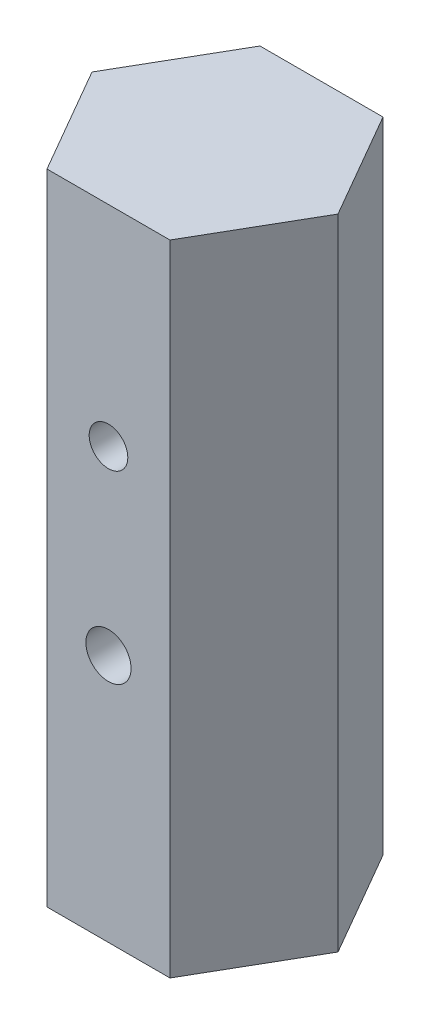
SolidWorks part; units mm, degrees
ref_plane "Front Plane" through (0, 0, 0) normal (0, 0, 1) x (1, 0, 0)
ref_plane "Top Plane" through (0, 0, 0) normal (0, 1, 0) x (1, 0, 0)
ref_plane "Right Plane" through (0, 0, 0) normal (1, 0, 0) x (0, 0, -1)
sketch "Sketch1" plane through (0, 0, 0) normal (0, 1, 0) x (1, 0, 0)
  line L1 (5.4993, -9.525) -> (10.9985, 0)
  line L2 (10.9985, 0) -> (5.4993, 9.525)
  line L3 (5.4993, 9.525) -> (-5.4993, 9.525)
  line L4 (-5.4993, 9.525) -> (-10.9985, 0)
  line L5 (-10.9985, 0) -> (-5.4993, -9.525)
  line L6 (-5.4993, -9.525) -> (5.4993, -9.525)
  circle A0 centre (0, 0) radius 9.525 construction
  dimension "D1" = 19.05
extrude "Boss-Extrude1" add sketch "Sketch1" along normal blind 57.15
hole_wizard "1/2 (0.5) Diameter Hole1" positions "Sketch4" profile "Sketch5" hole size "1/2" standard "ANSI Inch"
sketch "Sketch4" plane through (0, 0, 0) normal (0, -1, 0) x (-1, 0, 0)
  point P0 (0, 0)
sketch "Sketch5" plane through (0, 0, 0) normal (1, 0, 0) x (0, 0, -1)
  line L0 (0, 0) -> (0, 49.5355)
  line L1 (0, 49.5355) -> (6.35, 45.72)
  line L2 (6.35, 45.72) -> (6.35, 0)
  line L5 (6.35, 0) -> (0, 0)
  line L10 (0, 49.5355) -> (-6.35, 45.72) construction
  line L11 (0, -6.35) -> (0, 107.95) construction
  dimension "Hole Dia." = 12.7
  dimension "Hole Depth" = 45.72
  dimension "Drill Angle" = 118
hole_wizard "#10-32 Tapped Hole1" positions "Sketch7" profile "Sketch8" tap size "#10-32" standard "ANSI Inch"
sketch "Sketch7" plane through (0, 0, 9.525) normal (0, 0, 1) x (1, 0, 0)
  line L0 (-5.4993, 0) -> (5.4993, 0) construction
  point P0 (0, 22.225)
  point P5 (0, 0)
  dimension "D1" = 22.225
sketch "Sketch8" plane through (0, 22.225, 9.525) normal (1, 0, 0) x (0, -1, 0)
  line L0 (0, 0) -> (0, 3.175)
  line L1 (0, 3.175) -> (2.0193, 3.175)
  line L2 (2.0193, 3.175) -> (2.0193, 0)
  line L5 (2.0193, 0) -> (0, 0)
  line L11 (0, -6.35) -> (0, 107.95) construction
  dimension "Thru Tap Drill Dia." = 4.0386
  dimension "Thru Tap Drill Depth" = 3.175
cosmetic thread "Hole Thread1" parameters "D2"=4.826
hole_wizard "#29 (0.136) Diameter Hole1" positions "Sketch10" profile "Sketch11" hole size "#29" standard "ANSI Inch"
sketch "Sketch10" plane through (0, 0, 9.525) normal (0, 0, 1) x (1, 0, 0)
  line L0 (-5.4993, 0) -> (5.4993, 0) construction
  point P0 (0, 38.4175)
  dimension "D1" = 38.4175
sketch "Sketch11" plane through (0, 38.4175, 9.525) normal (1, 0, 0) x (0, -1, 0)
  line L0 (0, 0) -> (0, 3.175)
  line L1 (0, 3.175) -> (1.7272, 3.175)
  line L2 (1.7272, 3.175) -> (1.7272, 0)
  line L5 (1.7272, 0) -> (0, 0)
  line L11 (0, -6.35) -> (0, 107.95) construction
  dimension "Thru Hole Dia." = 3.4544
  dimension "Thru Hole Depth" = 3.175
